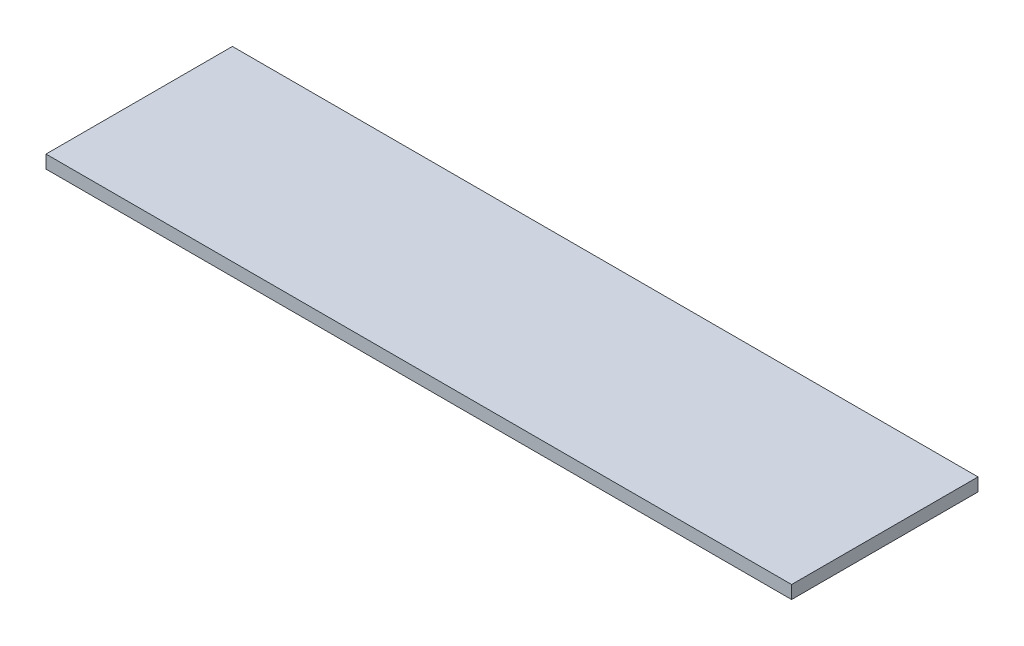
SolidWorks part; units mm, degrees
ref_plane "Front Plane" through (0, 0, 0) normal (0, 0, 1) x (1, 0, 0)
ref_plane "Top Plane" through (0, 0, 0) normal (0, 1, 0) x (1, 0, 0)
ref_plane "Right Plane" through (0, 0, 0) normal (1, 0, 0) x (0, 0, -1)
sketch "Sketch1" plane through (0, 0, 0) normal (0, 1, 0) x (1, 0, 0)
  line L1 (-20, -5) -> (20, -5)
  line L2 (-20, -5) -> (-20, 5)
  line L3 (-20, 5) -> (20, 5)
  line L4 (20, -5) -> (20, 5)
  line L5 (-20, -5) -> (20, 5) construction
  line L6 (-20, 5) -> (20, -5) construction
  point P0 (0, 0)
  dimension "D1" = 10
  dimension "D2" = 40
extrude "Boss-Extrude1" add sketch "Sketch1" along normal blind 0.7
